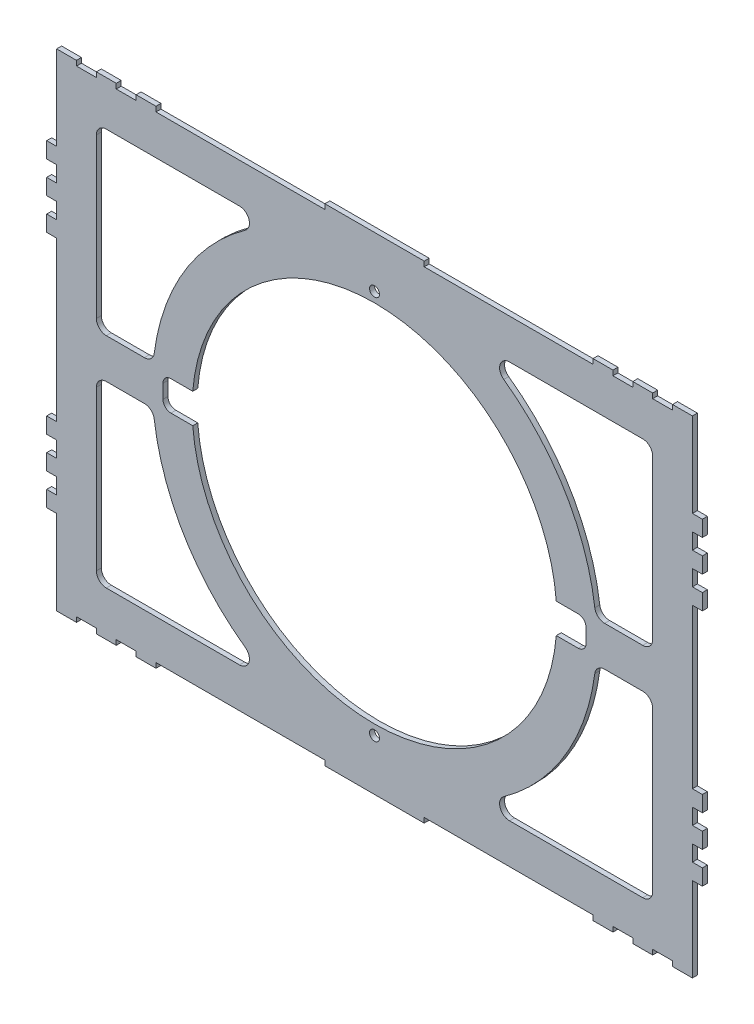
SolidWorks part; units mm, degrees
ref_plane "Front Plane" through (0, 0, 0) normal (0, 0, 1) x (1, 0, 0)
ref_plane "Top Plane" through (0, 0, 0) normal (0, 1, 0) x (1, 0, 0)
ref_plane "Right Plane" through (0, 0, 0) normal (1, 0, 0) x (0, 0, -1)
sketch "Sketch1" plane through (0, 0, 0) normal (0, 0, 1) x (1, 0, 0)
  line L0 (-209.55, 0) -> (209.55, 0) construction
  line L1 (-209.55, 155.575) -> (209.55, 155.575)
  line L2 (-209.55, 155.575) -> (-209.55, -155.575)
  line L3 (-209.55, -155.575) -> (209.55, -155.575)
  line L4 (209.55, 155.575) -> (209.55, -155.575)
  line L5 (-209.55, 155.575) -> (209.55, -155.575) construction
  line L6 (-209.55, -155.575) -> (209.55, 155.575) construction
  line L7 (0, 155.575) -> (0, -155.575) construction
  line L11 (-86.2969, 127) -> (-171.45, 127)
  line L12 (-177.8, 120.65) -> (-177.8, 19.05)
  line L13 (-171.45, 12.7) -> (-147.1077, 12.7)
  line L14 (-177.8, -120.65) -> (-177.8, -19.05)
  line L15 (-86.2969, -127) -> (-171.45, -127)
  line L16 (-171.45, -12.7) -> (-147.1077, -12.7)
  line L17 (86.2969, -127) -> (171.45, -127)
  line L18 (171.45, -12.7) -> (147.1077, -12.7)
  line L19 (177.8, -120.65) -> (177.8, -19.05)
  line L20 (177.8, 120.65) -> (177.8, 19.05)
  line L21 (86.2969, 127) -> (171.45, 127)
  line L22 (171.45, 12.7) -> (147.1077, 12.7)
  circle A0 centre (0, 0) radius 116.5733
  arc A4 (-82.6026, 115.4852) -> (-140.8103, 18.2345) centre (0, 0) ccw
  arc A5 (-82.6026, 115.4852) -> (-86.2969, 127) centre (-86.2969, 120.65) ccw
  arc A6 (-140.8103, 18.2345) -> (-147.1077, 12.7) centre (-147.1077, 19.05) cw
  arc A7 (-177.8, 19.05) -> (-171.45, 12.7) centre (-171.45, 19.05) ccw
  arc A8 (-171.45, 127) -> (-177.8, 120.65) centre (-171.45, 120.65) ccw
  arc A9 (-171.45, -127) -> (-177.8, -120.65) centre (-171.45, -120.65) cw
  arc A10 (-82.6026, -115.4852) -> (-86.2969, -127) centre (-86.2969, -120.65) cw
  arc A11 (-82.6026, -115.4852) -> (-140.8103, -18.2345) centre (0, 0) cw
  arc A12 (-140.8103, -18.2345) -> (-147.1077, -12.7) centre (-147.1077, -19.05) ccw
  arc A13 (-177.8, -19.05) -> (-171.45, -12.7) centre (-171.45, -19.05) cw
  arc A14 (171.45, -127) -> (177.8, -120.65) centre (171.45, -120.65) ccw
  arc A15 (82.6026, -115.4852) -> (86.2969, -127) centre (86.2969, -120.65) ccw
  arc A16 (82.6026, -115.4852) -> (140.8103, -18.2345) centre (0, 0) ccw
  arc A17 (140.8103, -18.2345) -> (147.1077, -12.7) centre (147.1077, -19.05) cw
  arc A18 (177.8, -19.05) -> (171.45, -12.7) centre (171.45, -19.05) ccw
  arc A19 (171.45, 127) -> (177.8, 120.65) centre (171.45, 120.65) cw
  arc A20 (82.6026, 115.4852) -> (86.2969, 127) centre (86.2969, 120.65) cw
  arc A21 (82.6026, 115.4852) -> (140.8103, 18.2345) centre (0, 0) cw
  arc A22 (140.8103, 18.2345) -> (147.1077, 12.7) centre (147.1077, 19.05) ccw
  arc A23 (177.8, 19.05) -> (171.45, 12.7) centre (171.45, 19.05) cw
  point P0 (0, 0)
  point P16 (-159.2788, 12.7)
  point P62 (0, 0)
  point P63 (0, 0)
  point P64 (0, 0)
  dimension "D3" = 233.1466
  dimension "D4" = 141.986
  dimension "D6" = 28.575
  dimension "D8" = 6.35
  dimension "D1" = 419.1
  dimension "D2" = 311.15
  dimension "D5" = 31.75
  dimension "D7" = 12.7
extrude "Boss-Extrude1" add sketch "Sketch1" along normal blind 3.175
sketch "Sketch2" plane through (0, 0, 3.175) normal (0, 0, 1) x (1, 0, 0)
  line L1 (55, 0) -> (-55, 0) construction
  circle A1 centre (0, 122.936) radius 3.175
  circle A2 centre (0, -122.936) radius 3.175
  point P0 (0, 126.7738)
  point P2 (0, 0)
  dimension "D1" = 122.936
  dimension "D2" = 6.35
extrude "Cut-Extrude1" cut sketch "Sketch2" against normal blind 3.175
sketch "Sketch3" plane through (0, 0, 3.175) normal (0, 0, 1) x (1, 0, 0)
  line L7 (116.1835, -9.525) -> (130.1535, -9.525)
  line L8 (135.2335, -4.445) -> (135.2335, 4.445)
  line L9 (130.1535, 9.525) -> (116.1835, 9.525)
  arc A0 (130.1535, -9.525) -> (135.2335, -4.445) centre (130.1535, -4.445) ccw
  circle A5 centre (0, 0) radius 116.5733 construction
  arc A6 (116.1835, 9.525) -> (116.1835, -9.525) centre (0, 0) cw
  arc A7 (135.2335, 4.445) -> (130.1535, 9.525) centre (130.1535, 4.445) ccw
  point P7 (114.4283, -35.2089)
  point P8 (0, 0)
  point P9 (146.9784, -4.0891)
  point P10 (0, 0)
  point P11 (0, 0)
  point P12 (0, 0)
  point P13 (135.2335, 0)
  point P16 (135.2335, -9.525)
  point P19 (135.2335, 9.525)
  dimension "D3" = 5.08
  dimension "D1" = 19.05
  dimension "D2" = 19.05
extrude "Cut-Extrude2" cut sketch "Sketch3" against normal blind 3.175
mirror "Mirror6" about plane through (0, 0, 0) normal (1, 0, 0) of "Cut-Extrude2"
sketch "Sketch4" plane through (0, 0, 3.175) normal (0, 0, 1) x (1, 0, 0)
  line L0 (209.55, 155.575) -> (-209.55, 155.575) construction
  line L1 (-31.75, 155.575) -> (-139.7, 155.575)
  line L2 (-31.75, 155.575) -> (-31.75, 152.4)
  line L3 (-31.75, 152.4) -> (-139.7, 152.4)
  line L4 (-139.7, 155.575) -> (-139.7, 152.4)
  line L5 (-209.55, 155.575) -> (-209.55, -155.575) construction
  line L6 (-190.5, 155.575) -> (-190.5, 152.4)
  line L7 (-215.9, 155.575) -> (-203.2, 155.575)
  line L8 (-215.9, 155.575) -> (-215.9, 152.4)
  line L9 (-215.9, 152.4) -> (-203.2, 152.4)
  line L10 (-203.2, 155.575) -> (-203.2, 152.4)
  line L11 (-190.5, 155.575) -> (-177.8, 155.575)
  line L12 (-177.8, 155.575) -> (-177.8, 152.4)
  line L13 (-190.5, 152.4) -> (-177.8, 152.4)
  line L14 (-165.1, 155.575) -> (-165.1, 152.4)
  line L15 (-165.1, 155.575) -> (-152.4, 155.575)
  line L16 (-152.4, 155.575) -> (-152.4, 152.4)
  line L17 (-165.1, 152.4) -> (-152.4, 152.4)
  point P12 (-209.55, 155.575)
  dimension "D1" = 3.175
  dimension "2.5" = 107.95
  dimension "D2" = 69.85
  dimension "D3" = 12.7
  dimension "D4" = 3.175
  dimension "D6" = 12.7
  dimension "D5" = 3
extrude "Cut-Extrude3" cut sketch "Sketch4" against normal blind 3.175
mirror "Mirror2" about plane through (0, 0, 0) normal (1, 0, 0) of "Cut-Extrude3"
mirror "Mirror3" about plane through (0, 0, 0) normal (0, 1, 0) of "Cut-Extrude3", "Mirror2"
sketch "Sketch6" plane through (0, 0, 3.175) normal (0, 0, 1) x (1, 0, 0)
  line L0 (-209.55, 152.4) -> (-209.55, -152.4) construction
  line L1 (-209.55, 152.4) -> (-203.2, 152.4)
  line L2 (-209.55, 152.4) -> (-209.55, 101.6)
  line L3 (-209.55, 101.6) -> (-203.2, 101.6)
  line L4 (-203.2, 152.4) -> (-203.2, 101.6)
  line L5 (-209.55, 50.8) -> (-203.2, 50.8)
  line L6 (-209.55, 50.8) -> (-209.55, 0)
  line L7 (-209.55, 0) -> (-203.2, 0)
  line L8 (-203.2, 50.8) -> (-203.2, 0)
  line L15 (-209.55, 91.44) -> (-203.2, 91.44)
  line L16 (-209.55, 91.44) -> (-209.55, 81.28)
  line L17 (-209.55, 81.28) -> (-203.2, 81.28)
  line L18 (-203.2, 91.44) -> (-203.2, 81.28)
  line L23 (-209.55, 71.12) -> (-203.2, 71.12)
  line L24 (-209.55, 71.12) -> (-209.55, 60.96)
  line L25 (-209.55, 60.96) -> (-203.2, 60.96)
  line L26 (-203.2, 71.12) -> (-203.2, 60.96)
  dimension "D1" = 50.8
  dimension "D2" = 6.35
  dimension "D3" = 10.16
  dimension "D4" = 10.16
  dimension "D5" = 50.8
  dimension "D6" = 6.35
  dimension "D7" = 6.35
  dimension "D8" = 10.16
  dimension "D9" = 10.16
extrude "Cut-Extrude4" cut sketch "Sketch6" against normal blind 3.175
mirror "Mirror4" about plane through (0, 0, 0) normal (1, 0, 0) of "Cut-Extrude4"
mirror "Mirror5" about plane through (0, 0, 0) normal (0, 1, 0) of "Cut-Extrude4", "Mirror4"
